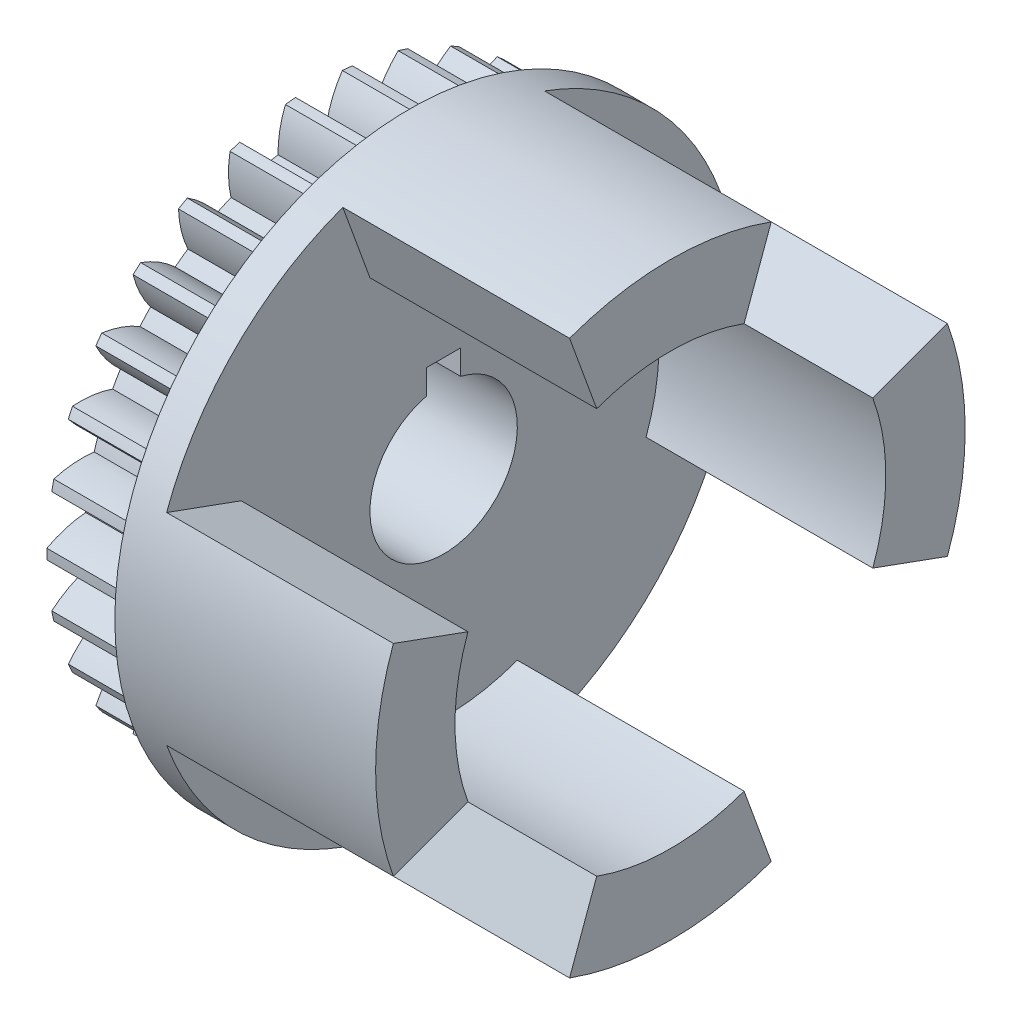
SolidWorks part; units mm, degrees
ref_plane "Plane1" through (0, 0, 0) normal (0, 0, 1) x (1, 0, 0)
ref_plane "Plane2" through (0, 0, 0) normal (0, 1, 0) x (1, 0, 0)
ref_plane "Plane3" through (0, 0, 0) normal (1, 0, 0) x (0, 0, -1)
sketch "HoldingSke" plane through (0, 0, 0) normal (0, 1, 0) x (1, 0, 0)
  line L0 (0, 0) -> (0.5774, -0.3333)
  line L1 (-15, 0) -> (100, 0) construction
  line L2 (0, 0) -> (-2.1039, 2.3779)
  line L3 (0, 0) -> (-11.863, 4.5341)
  line L4 (0, 0) -> (7.479, 4.318)
  line L5 (0, 0) -> (-46.8476, -17.4728)
  line L6 (0, 0) -> (-6.6317, -4.4744)
  line L7 (-2.1039, 2.3779) -> (8.6586, 51.2059)
  line L8 (-76.2, 54.61) -> (-75.5, 54.61)
  line L9 (-71.009, 38.7566) -> (-53.1078, 45.2721)
  line L10 (-76.2, 71.12) -> (104.1128, 71.12)
  line L11 (0, 0) -> (-8, 0)
  line L12 (-76.2, 101.6) -> (-76.147, 101.6)
  line L13 (24.9733, 27.94) -> (52.9518, 28.4284)
  line L14 (24.9733, 27.94) -> (24.9743, 27.94)
  line L15 (24.9733, 27.94) -> (100.4006, 29.5858)
  line L16 (-63.627, -1.5) -> (-12.827, -1.5)
  circle A0 centre (0, 0) radius 2
  circle A1 centre (0, 0) radius 20.624
  circle A2 centre (0, 0) radius 37.5
  circle A3 centre (0, 0) radius 2
  dimension "MHD" = 41.248
  dimension "Hub_dia" = 75
  dimension "Bore" = 4
  dimension "MBD" = 4
  dimension "Num_teeth" = 30
  dimension "Pitch" = 0.6667
  dimension "Overall_len" = 50
  dimension "Show_teeth" = 30
  dimension "Thickness" = 8
  dimension "OAL" = 50.0001
  dimension "T_dim" = 0.7
  dimension "Ap" = 20
  dimension "H" = 19.05
  dimension "Pitch_radius" = 180.3128
  dimension "Width" = 8
  dimension "Backlash" = 0.053
  dimension "Addendum_fac" = 1
  dimension "Dedendum_fac" = 1.25
  dimension "Clearance_fac" = 0.25
  dimension "Dedendum_add" = 0.001
  dimension "Module" = 1.5
sketch "BasProSke" plane through (0, 0, 0) normal (0, 1, 0) x (1, 0, 0)
  line L0 (-10, 0) -> (60, 0) construction
  line L1 (0, 0) -> (0, 24)
  line L2 (0, 0) -> (8, 0)
  line L3 (8, 0) -> (8, 24)
  line L4 (8, 24) -> (0, 24)
  dimension "Thickness" = 8
  dimension "Diameter" = 48
revolve "Base-Revolve" add sketch "BasProSke" angle 360 about L0
sketch "TooCutSke" plane through (0, 0, 0) normal (1, 0, 0) x (0, 0, -1)
  line L1 (0, 0) -> (0, 107) construction
  line L2 (0, 0) -> (-1.2703, 22.4641) construction
  line L3 (0, 0) -> (-4.6983, 44.7014) construction
  line L4 (-1.2703, 22.4641) -> (-2.3492, 22.3507) construction
  arc A0 (0.6933, 20.6123) -> (-0.6933, 20.6123) centre (0, 0) ccw
  arc A1 (2.0805, 23.9351) -> (-2.0805, 23.9351) centre (0, 0) ccw
  circle A2 centre (0, 0) radius 22.5 construction
  circle A3 centre (0, 0) radius 21.1431 construction
  arc A4 (-0.6933, 20.6123) -> (-2.0805, 23.9351) centre (-9.5243, 18.8764) ccw
  arc A5 (2.0805, 23.9351) -> (0.6933, 20.6123) centre (9.5243, 18.8764) ccw
  dimension "Root_dia" = 41.248
  dimension "Overcut_dia" = 48.0508
  dimension "Pitch_dia" = 45
  dimension "Base_dia" = 42.2862
  dimension "Flank_rad" = 9
  dimension "Half_ang" = 6
  dimension "Half_CT" = 1.0848
extrude "ToothCut" cut sketch "TooCutSke" along normal through all
fillet "Breaks" [suppressed] radius 0.03
fillet "RootFillets" [suppressed] radius 0.376
pattern_circular "TeethCuts" count 30 every 12 about axis through (-10, 0, 0) along (1, 0, 0) of "ToothCut", "RootFillets", "Breaks"
sketch "HubNeaOneSke" plane through (0, 0, 0) normal (-1, 0, 0) x (0, 0, 1)
  circle A0 centre (0, 0) radius 20.624
  dimension "Diameter" = 41.248
extrude "HubNearOne" [suppressed] add sketch "HubNeaOneSke" along normal blind 42.0001
sketch "HubNeaBotSke" plane through (0, 0, 0) normal (-1, 0, 0) x (0, 0, 1)
  circle A0 centre (0, 0) radius 20.624
  dimension "Diameter" = 41.248
extrude "HubNearBoth" [suppressed] add sketch "HubNeaBotSke" along normal blind 21
ref_plane "FarPln" through (8, 0, 0) normal (1, 0, 0) x (0, 0, -1)
sketch "HubFarSke" plane through (8, 0, 0) normal (1, 0, 0) x (0, 0, -1)
  circle A0 centre (0, 0) radius 20.624
  dimension "Diameter" = 41.248
extrude "HubFar" [suppressed] add sketch "HubFarSke" along normal blind 21
sketch "BorSke" plane through (0, 0, 0) normal (1, 0, 0) x (0, 0, -1)
  circle A0 centre (0, 0) radius 2
  dimension "Diameter" = 4
extrude "Bore" cut sketch "BorSke" along normal mid plane 100.0001
sketch "KeySke" plane through (0, 0, 0) normal (1, 0, 0) x (0, 0, -1)
  line L0 (-0.8, 0) -> (-0.8, 2.7)
  line L1 (-0.8, 2.7) -> (0.8, 2.7)
  line L2 (0.8, 2.7) -> (0.8, 0)
  line L3 (0, 0) -> (0, 34) construction
  line L4 (-0.8, 0) -> (0.8, 0)
  dimension "Offset" = 2.7
  dimension "Width" = 1.6
extrude "Keyway" [suppressed] cut sketch "KeySke" along normal mid plane 100.0001
pattern_circular "Keyway2" [suppressed] count 2 every 90 about axis through (-10, 0, 0) along (1, 0, 0)
sketch "草图1" plane through (8, 0, 0) normal (1, 0, 0) x (0, 0, -1)
  circle A0 centre (0, 0) radius 26
  dimension "D1" = 52
extrude "凸台-拉伸1" add sketch "草图1" along normal blind 3
sketch "草图2" plane through (11, 0, 0) normal (1, 0, 0) x (0, 0, -1)
  line L0 (-6.4984, 17.8542) -> (-8.8925, 24.432)
  line L1 (0, 27.9555) -> (0, 19) construction
  line L2 (6.4984, 17.8542) -> (8.8925, 24.432)
  line L3 (0, 0) -> (-6.4984, 17.8542) construction
  line L4 (0, 19) -> (0, 0) construction
  line L5 (0, -19) -> (0, -29.6234) construction
  line L6 (0, 0) -> (6.4984, 17.8542) construction
  line L7 (0, 0) -> (0, -19) construction
  line L8 (17.8542, -6.4984) -> (24.432, -8.8925)
  line L9 (17.8542, 6.4984) -> (24.432, 8.8925)
  line L10 (-6.4984, -17.8542) -> (-8.8925, -24.432)
  line L11 (6.4984, -17.8542) -> (8.8925, -24.432)
  line L12 (-17.8542, 6.4984) -> (-24.432, 8.8925)
  line L13 (-17.8542, -6.4984) -> (-24.432, -8.8925)
  arc A0 (6.4984, 17.8542) -> (-6.4984, 17.8542) centre (0, 0) ccw
  circle A1 centre (0, 0) radius 26 construction
  arc A2 (0, -19) -> (6.4984, 17.8542) centre (0, 0) ccw construction
  arc A3 (-6.4984, 17.8542) -> (0, -19) centre (0, 0) ccw construction
  arc A4 (-8.8925, 24.432) -> (8.8925, 24.432) centre (0, 0) cw
  arc A5 (24.432, 8.8925) -> (24.432, -8.8925) centre (0, 0) cw
  arc A6 (17.8542, -6.4984) -> (17.8542, 6.4984) centre (0, 0) ccw
  arc A7 (8.8925, -24.432) -> (-8.8925, -24.432) centre (0, 0) cw
  arc A8 (-6.4984, -17.8542) -> (6.4984, -17.8542) centre (0, 0) ccw
  arc A9 (-24.432, -8.8925) -> (-24.432, 8.8925) centre (0, 0) cw
  arc A10 (-17.8542, 6.4984) -> (-17.8542, -6.4984) centre (0, 0) ccw
  point P27 (0, 0)
  dimension "D1" = 38
  dimension "D2" = 40
  dimension "D3" = 4
extrude "凸台-拉伸2" add sketch "草图2" along normal blind 20
sketch "草图3" plane through (11, 0, 0) normal (1, 0, 0) x (0, 0, -1)
  line L0 (-1.5, 4.5) -> (-1.5, 6.3246) construction
  line L1 (-1.5, 4.5) -> (1.5, 4.5) construction
  line L2 (-1.5, 6.3246) -> (-1.5, 8.5)
  line L3 (-1.5, 8.5) -> (1.5, 8.5)
  line L4 (1.5, 6.3246) -> (1.5, 8.5)
  line L5 (0, 6.5) -> (1.5, 8.5) construction
  line L6 (-1.5, 8.5) -> (0, 6.5) construction
  line L7 (-1.5, 4.5) -> (0, 6.5) construction
  line L8 (0, 6.5) -> (1.5, 4.5) construction
  line L9 (1.5, 4.5) -> (1.5, 6.3246) construction
  arc A0 (-1.5, 6.3246) -> (1.5, 6.3246) centre (0, 0) ccw
  arc A1 (0, 6.5) -> (-1.5, 6.3246) centre (0, 0) ccw construction
  arc A2 (1.5, 6.3246) -> (0, 6.5) centre (0, 0) ccw construction
  point P3 (0, 6.5)
  dimension "D1" = 13
  dimension "D2" = 3
  dimension "D3" = 2
extrude "切除-拉伸1" cut sketch "草图3" against normal through all
equation "' \"Module@HoldingSke\" = 6.35"
equation "' \"Num_teeth@HoldingSke\" = 12"
equation "' \"Ap@HoldingSke\" =  20"
equation "' \"Ap@HoldingSke\" = 20"
equation "' \"Width@HoldingSke\" = 0.5 * 25.4"
equation "' \"Hub_dia@HoldingSke\"= 1 * 25.4"
equation "' \"Hub_dia@HoldingSke\" = 1 * 25.4"
equation "' \"Overall_len@HoldingSke\" = 1.0 * 25.4"
equation "' \"Bore@HoldingSke\" = 0.75 * 25.4"
equation "' \"T_dim@HoldingSke\" = 0.1 * 25.4"
equation "' \"Width@KeySke\" = 0.25 * 25.4"
equation "' \"Show_teeth@HoldingSke\" = 13"
equation "' \"Backlash@HoldingSke\" = 0.009 * 25.4"
equation "' \"Addendum_fac@HoldingSke\" = 1.0"
equation "' \"Dedendum_fac@HoldingSke\" = 1.25"
equation "' \"Dedendum_add@HoldingSke\" = 0.00005 * 25.4"
equation "' \"Clearance_fac@HoldingSke\" = 0.25"
equation "\"Pitch@HoldingSke\" = 1 / \"Module@HoldingSke\""
equation "\"Overcut_dia@TooCutSke\" = (\"Num_teeth@HoldingSke\" + 2 * \"Addendum_fac@HoldingSke\") / \"Pitch@HoldingSke\" + 0.002 * 25.4"
equation "\"Pitch_dia@TooCutSke\" = \"Num_teeth@HoldingSke\" / \"Pitch@HoldingSke\""
equation "\"Base_dia@TooCutSke\" = \"Num_teeth@HoldingSke\" / \"Pitch@HoldingSke\" * cos((\"Ap@HoldingSke\"  * 3.14159265 / 180))"
equation "\"Root_dia@TooCutSke\" = (\"Num_teeth@HoldingSke\" + 2) / \"Pitch@HoldingSke\" - 2 * (\"Addendum_fac@HoldingSke\" + \"Dedendum_fac@HoldingSke\") / \"Pitch@HoldingSke\" - \"Dedendum_add@HoldingSke\" * 2"
equation "\"Half_ang@TooCutSke\" = 180 / \"Num_teeth@HoldingSke\""
equation "\"Half_CT@TooCutSke\" = \"Num_teeth@HoldingSke\" / \"Pitch@HoldingSke\" * sin((3.14159265 / 2 / \"Num_teeth@HoldingSke\")) / 2 - 7 * \"Backlash@HoldingSke\" / 4"
equation "\"Flank_rad@TooCutSke\" = \"Num_teeth@HoldingSke\" / \"Pitch@HoldingSke\" / 5"
equation "\"Radius@RootFillets\" = \"Clearance_fac@HoldingSke\" / \"Pitch@HoldingSke\" + \"Dedendum_add@HoldingSke\""
equation "\"Break_rad@Breaks\" = 0.02 / \"Pitch@HoldingSke\""
equation "\"Thickness@HoldingSke\" = \"Width@HoldingSke\""
equation "\"OAL@HoldingSke\" = \"Thickness@HoldingSke\""
equation "\"MHD@HoldingSke\" = (\"Num_teeth@HoldingSke\" + 2) / \"Pitch@HoldingSke\" - 2 * (\"Addendum_fac@HoldingSke\" + \"Dedendum_fac@HoldingSke\")  / \"Pitch@HoldingSke\" - \"Dedendum_add@HoldingSke\" * 2"
equation "\"MBD@HoldingSke\" = (\"Num_teeth@HoldingSke\" + 2) / \"Pitch@HoldingSke\" - 2 * (\"Addendum_fac@HoldingSke\" + \"Dedendum_fac@HoldingSke\")  / \"Pitch@HoldingSke\" - \"Dedendum_add@HoldingSke\" * 2 - 0.002 * 25.4"
equation "\"MHD@HoldingSke\" = ((sgn( \"MHD@HoldingSke\" - \"Hub_dia@HoldingSke\" )-1)*( \"MHD@HoldingSke\" - \"Hub_dia@HoldingSke\" ))/-2+ \"Hub_dia@HoldingSke\""
equation "\"MBD@HoldingSke\" = ((sgn( \"MBD@HoldingSke\" - \"Bore@HoldingSke\" )-1)*( \"MBD@HoldingSke\" - \"Bore@HoldingSke\" ))/-2+ \"Bore@HoldingSke\""
equation "\"OAL@HoldingSke\" = ((sgn( \"OAL@HoldingSke\" - \"Overall_len@HoldingSke\" )+1)*( \"OAL@HoldingSke\" - \"Overall_len@HoldingSke\" ))/2 + \"Overall_len@HoldingSke\" + 0.000002 * 25.4"
equation "\"Num_teeth@TeethCuts\" = int( \"Show_teeth@HoldingSke\" ) + 1"
equation "\"Num_teeth@TeethCuts\" = ((sgn( \"Num_teeth@TeethCuts\" - \"Num_teeth@HoldingSke\" )-1)*( \"Num_teeth@TeethCuts\" - \"Num_teeth@HoldingSke\" ))/-2+ \"Num_teeth@HoldingSke\""
equation "\"Num_teeth@TeethCuts\" = ((sgn( \"Num_teeth@TeethCuts\" - 2.0)+1)*( \"Num_teeth@TeethCuts\" - 2.0))/2 +2.0"
equation "\"Angle@TeethCuts\" = 360.0 / \"Num_teeth@HoldingSke\""
equation "\"Diameter@BasProSke\" = (\"Num_teeth@HoldingSke\" + 2 * \"Addendum_fac@HoldingSke\") / \"Pitch@HoldingSke\""
equation "\"Thickness@BasProSke\"  = \"Thickness@HoldingSke\""
equation "' \"Fillet_rad@BasProSke\" =  \"Thickness@HoldingSke\" * 0.05"
equation "' \"Fillet_rad@BasProSke\" = \"Thickness@HoldingSke\" * 0.05"
equation "\"MHD@HoldingSke\" = ((sgn( \"MHD@HoldingSke\" - \"Root_dia@TooCutSke\" )-1)*( \"MHD@HoldingSke\" - \"Root_dia@TooCutSke\" ))/-2+ \"Root_dia@TooCutSke\""
equation "\"Diameter@HubNeaOneSke\" = \"MHD@HoldingSke\""
equation "\"Length@HubNearOne\" = \"OAL@HoldingSke\" - \"Thickness@BasProSke\""
equation "\"Diameter@HubNeaBotSke\" = \"MHD@HoldingSke\""
equation "\"Length@HubNearBoth\" = ( \"OAL@HoldingSke\" - \"Thickness@BasProSke\" ) / 2.0"
equation "\"Thickness@FarPln\" = \"Thickness@BasProSke\""
equation "\"Diameter@HubFarSke\" = \"MHD@HoldingSke\""
equation "\"Length@HubFar\" = ( \"OAL@HoldingSke\" - \"Thickness@BasProSke\" ) / 2.0"
equation "\"Diameter@BorSke\" = \"MBD@HoldingSke\""
equation "\"D1@Bore\" = \"OAL@HoldingSke\" * 2.0"
equation "\"D1@Keyway\" = \"OAL@HoldingSke\" * 2.0"
equation "\"Offset@KeySke\" = \"T_dim@HoldingSke\" + \"MBD@HoldingSke\" / 2.0"
